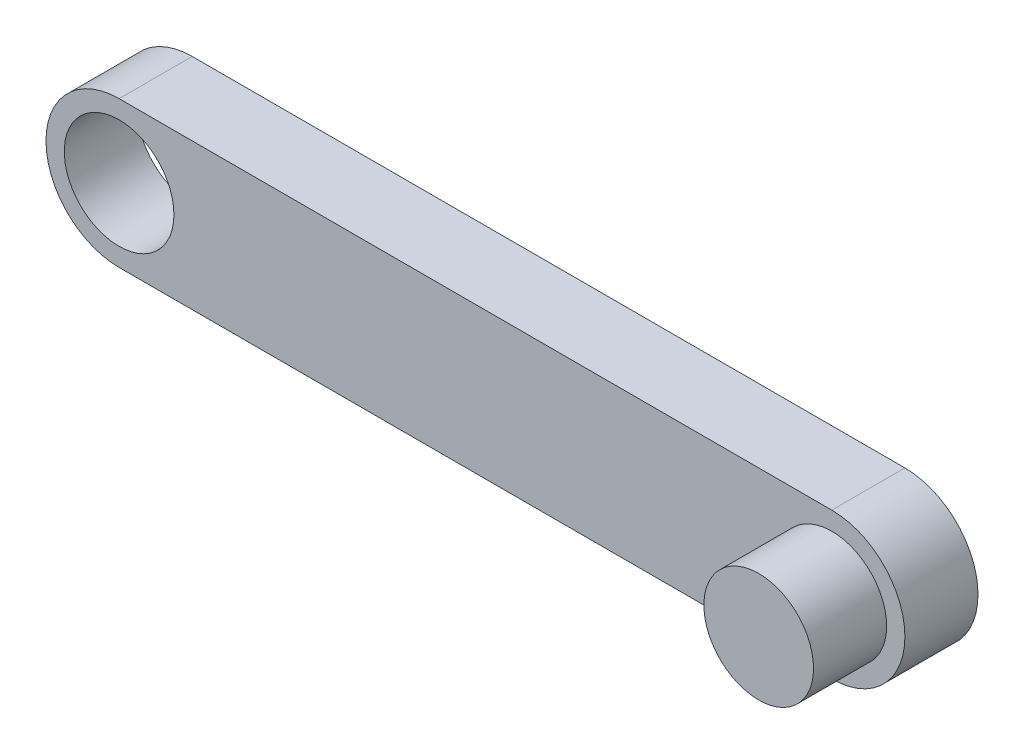
SolidWorks part; units mm, degrees
ref_plane "Front Plane" through (0, 0, 0) normal (0, 0, 1) x (1, 0, 0)
ref_plane "Top Plane" through (0, 0, 0) normal (0, 1, 0) x (1, 0, 0)
ref_plane "Right Plane" through (0, 0, 0) normal (1, 0, 0) x (0, 0, -1)
sketch "Sketch1" plane through (0, 0, 0) normal (0, 0, 1) x (1, 0, 0)
  line L1 (97.5, 20) -> (-97.5, 20)
  line L3 (97.5, -20) -> (-97.5, -20)
  arc A0 (-97.5, 20) -> (-97.5, -20) centre (-97.5, 0) ccw
  arc A1 (97.5, -20) -> (97.5, 20) centre (97.5, 0) ccw
  point P0 (0, 0)
  dimension "D1" = 195
  dimension "D2" = 40
extrude "Boss-Extrude1" add sketch "Sketch1" along normal blind 20
sketch "Sketch2" plane through (0, 0, 20) normal (0, 0, 1) x (1, 0, 0)
  circle A0 centre (-97.5, 0) radius 15
extrude "Cut-Extrude1" cut sketch "Sketch2" against normal blind 20
sketch "Sketch3" plane through (0, 0, 20) normal (0, 0, 1) x (1, 0, 0)
  circle A0 centre (97.5, 0) radius 15
extrude "Boss-Extrude2" add sketch "Sketch3" along normal blind 20
sketch "Sketch5" plane through (0, 0, 20) normal (0, 0, 1) x (1, 0, 0)
  point P0 (97.5, 0)
